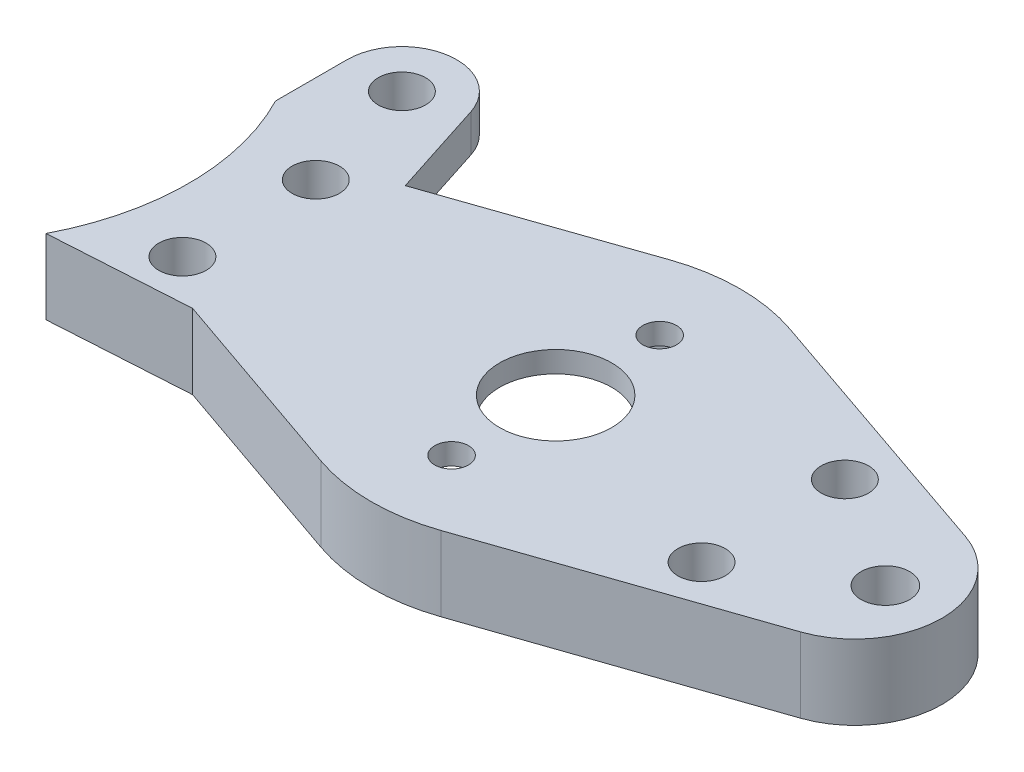
SolidWorks part; units mm, degrees
ref_plane "Front Plane" through (0, 0, 0) normal (0, 0, 1) x (1, 0, 0)
ref_plane "Top Plane" through (0, 0, 0) normal (0, 1, 0) x (1, 0, 0)
ref_plane "Right Plane" through (0, 0, 0) normal (1, 0, 0) x (0, 0, -1)
sketch "Sketch1" plane through (0, 0, 0) normal (0, 1, 0) x (1, 0, 0)
  line L36 (11.0898, 8.53) -> (11.0898, -8.53) construction
  line L37 (0, 9.2083) -> (0, -9.2083) construction
  line L38 (7.0898, 5.35) -> (7.0898, -5.35) construction
  line L49 (11.0898, 8.53) -> (26.8479, 13.9856)
  line L50 (0, 0) -> (31.6898, 0) construction
  line L52 (0, 9.2083) -> (11.0898, 8.53)
  line L54 (0, -9.2083) -> (11.0898, -8.53)
  line L55 (11.0898, -8.53) -> (26.8479, -13.9856)
  line L56 (31.6898, 0) -> (55.6898, 0) construction
  line L57 (36.4998, 13.9966) -> (57.9648, 6.62)
  line L58 (36.4998, -13.9966) -> (57.9648, -6.62)
  line L59 (55.6898, 0) -> (58.1477, 0) construction
  line L60 (49.1477, -5.75) -> (49.1477, 5.75) construction
  circle A2 centre (7.0898, -5.35) radius 1.9
  circle A6 centre (7.0898, 5.35) radius 1.9
  circle A7 centre (31.6898, 0) radius 12.3 construction
  arc A8 (36.4998, 13.9966) -> (36.4998, -13.9966) centre (31.6898, 0) ccw
  arc A9 (57.9648, -6.62) -> (57.9648, 6.62) centre (55.6898, 0) ccw
  circle A12 centre (49.1477, 5.75) radius 1.9
  circle A13 centre (49.1477, -5.75) radius 1.9
  circle A15 centre (58.1477, 0) radius 1.95
  arc A16 (11.0898, -8.53) -> (11.0898, 8.53) centre (-7, 0) ccw construction
  arc A17 (0, -9.2083) -> (0, 9.2083) centre (-17.7541, 0) ccw
  point P3 (11.0898, 0)
  point P10 (7.0898, 0)
  point P20 (0, 0)
  point P30 (49.1477, 0)
  point P36 (13, 0)
  dimension "D3" = 3.8
  dimension "D4" = 93.5
  dimension "D6" = 24.6
  dimension "D7" = 24.6
  dimension "D14" = 11.5
  dimension "D8" = 2.5
  dimension "D11" = 7
  dimension "D12" = 3.9
  dimension "D13" = 3.8
  dimension "D16" = 20
  dimension "D5" = 13
  dimension "D9" = 10.7
  dimension "D10" = 4
  dimension "D15" = 17.06
  dimension "D17" = 17.4579
  dimension "D18" = 2.4579
  dimension "D20" = 24
extrude "Boss-Extrude1" add sketch "Sketch1" along normal blind 6
sketch "Sketch2" plane through (0, 0, 0) normal (0, 1, 0) x (1, 0, 0)
  circle A0 centre (31.6898, 0) radius 12.3
  dimension "D1" = 24.6
extrude "Cut-Extrude1" cut sketch "Sketch2" along normal offset from surface (4.3 mm away) 1.7 up to face at (27.1773, 6, 0)
sketch "Sketch5" plane through (0, 0, 0) normal (0, 1, 0) x (1, 0, 0)
  line L0 (31.6898, -8.35) -> (31.6898, 8.35) construction
  circle A0 centre (31.6898, 0) radius 14.8 construction
  circle A1 centre (31.6898, 8.35) radius 1.35
  circle A2 centre (31.6898, -8.35) radius 1.35
  circle A3 centre (31.6898, 0) radius 4.5
  point P6 (31.6898, 0)
  dimension "D1" = 2.7
  dimension "D3" = 9
  dimension "D2" = 16.7
extrude "Cut-Extrude3" cut sketch "Sketch5" along normal up to surface (6 mm away) up to face at (27.1773, 6, 0)
sketch "Sketch6" plane through (0, 6, 0) normal (0, 1, 0) x (1, 0, 0)
  line L3 (0, 9.2083) -> (0, 14.9504)
  line L6 (0, 9.2083) -> (11.0898, 8.53) construction
  line L7 (11.0898, 8.53) -> (8.5882, 16.2989)
  arc A1 (8.5882, 16.2989) -> (0, 14.9504) centre (4.4, 14.9504) ccw
  circle A2 centre (4.4, 14.9504) radius 1.9
  point P3 (4.7964, 14.4602)
  point P5 (4.4941, 15.285)
  point P8 (10.3587, 13.2495)
  point P9 (4.4, 15.2509)
  point P12 (5.5315, 15.174)
  point P14 (5.1888, 18.0045)
  point P15 (5.628, 17.2998)
  point P16 (11.4071, 11.1146)
  point P17 (1.7607, 17.5014)
  point P18 (6.294, 18.3919)
  point P19 (5.8067, 12.1977)
  point P20 (3.4607, 20.2537)
  point P21 (5.0392, 12.4824)
  point P22 (4.5403, 13.899)
  dimension "D1" = 3.8
  dimension "D2" = 2.5
  dimension "D3" = 6
extrude "Boss-Extrude3" add sketch "Sketch6" against normal blind 3
